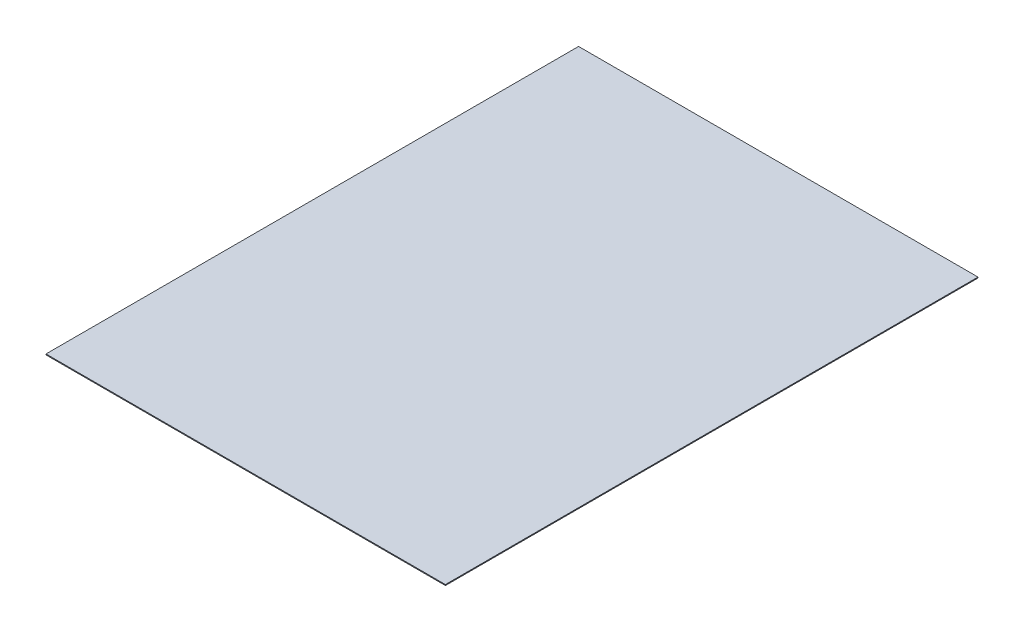
SolidWorks part; units mm, degrees
ref_plane "Front Plane" through (0, 0, 0) normal (0, 0, 1) x (1, 0, 0)
ref_plane "Top Plane" through (0, 0, 0) normal (0, 1, 0) x (1, 0, 0)
ref_plane "Right Plane" through (0, 0, 0) normal (1, 0, 0) x (0, 0, -1)
sketch "Sketch1" plane through (0, 0, 0) normal (0, 1, 0) x (1, 0, 0)
  line L1 (-44.3957, 30.5888) -> (855.6043, 30.5888)
  line L2 (-44.3957, 30.5888) -> (-44.3957, -1169.4112)
  line L3 (-44.3957, -1169.4112) -> (855.6043, -1169.4112)
  line L4 (855.6043, 30.5888) -> (855.6043, -1169.4112)
  line L5 (-44.3957, 30.5888) -> (855.6043, -1169.4112) construction
  line L6 (-44.3957, -1169.4112) -> (855.6043, 30.5888) construction
  point P0 (405.6043, -569.4112)
  dimension "D1" = 900
  dimension "D2" = 1200
extrude "Boss-Extrude1" add sketch "Sketch1" along normal blind 2
